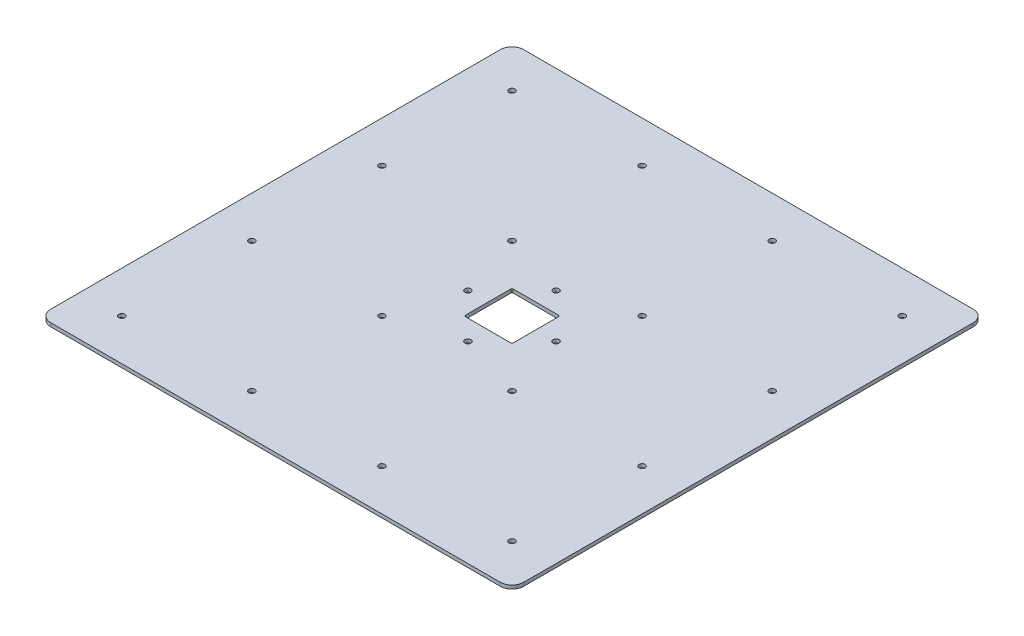
SolidWorks part; units mm, degrees
material "Stainless Steel (ferritic)"
ref_plane "Front Plane" through (0, 0, 0) normal (0, 0, 1) x (1, 0, 0)
ref_plane "Top Plane" through (0, 0, 0) normal (0, 1, 0) x (1, 0, 0)
ref_plane "Right Plane" through (0, 0, 0) normal (1, 0, 0) x (0, 0, -1)
sketch "Sketch1" plane through (0, 0, 0) normal (0, 1, 0) x (1, 0, 0)
  line L1 (-200, 200) -> (200, 200)
  line L2 (-200, 200) -> (-200, -200)
  line L3 (-200, -200) -> (200, -200)
  line L4 (200, 200) -> (200, -200)
  line L5 (-200, 200) -> (200, -200) construction
  line L6 (-200, -200) -> (200, 200) construction
  point P0 (0, 0)
  dimension "D1" = 400
  dimension "D2" = 400
extrude "Boss-Extrude1" add sketch "Sketch1" along normal blind 3
sketch "Sketch3" plane through (0, 3, 0) normal (0, 1, 0) x (1, 0, 0)
  line L1 (-19.25, 20.25) -> (19.25, 20.25)
  line L2 (-20.25, 19.25) -> (-20.25, -19.25)
  line L3 (-19.25, -20.25) -> (19.25, -20.25)
  line L4 (20.25, 19.25) -> (20.25, -19.25)
  line L5 (-20.25, 20.25) -> (20.25, -20.25) construction
  line L6 (-20.25, -20.25) -> (20.25, 20.25) construction
  arc A0 (19.25, -20.25) -> (20.25, -19.25) centre (19.25, -19.25) ccw
  arc A1 (-20.25, -19.25) -> (-19.25, -20.25) centre (-19.25, -19.25) ccw
  arc A2 (19.25, 20.25) -> (20.25, 19.25) centre (19.25, 19.25) cw
  arc A3 (-19.25, 20.25) -> (-20.25, 19.25) centre (-19.25, 19.25) ccw
  point P0 (0, 0)
  dimension "D3" = 1
  dimension "D1" = 40.5
  dimension "D2" = 40.5
extrude "Cut-Extrude1" cut sketch "Sketch3" against normal through all
sketch "Sketch4" plane through (0, 3, 0) normal (0, 1, 0) x (1, 0, 0)
  line L0 (0, 0) -> (-37.25, 0) construction
  line L1 (-20.25, 19.25) -> (-20.25, -19.25) construction
  line L2 (0, 0) -> (-37.25, 0) construction
  line L3 (0, 0) -> (0, 37.25) construction
  circle A0 centre (-37.25, 0) radius 2.58
  circle A1 centre (0, 37.25) radius 2.58
  circle A2 centre (37.25, 0) radius 2.58
  circle A3 centre (0, -37.25) radius 2.58
  point P4 (-20.25, 0)
  dimension "D1" = 5.16
  dimension "D2" = 17
  dimension "D4" = 90
  dimension "D5" = 37.25
  dimension "D3" = 4
extrude "Cut-Extrude2" cut sketch "Sketch4" against normal through all
sketch "Sketch9" plane through (0, 3, 0) normal (0, 1, 0) x (1, 0, 0)
  line L0 (-165, 165) -> (-200, 165) construction
  line L1 (-200, 200) -> (-200, -200) construction
  line L2 (-165, 165) -> (-165, 200) construction
  line L3 (200, 200) -> (-200, 200) construction
  line L4 (-165, 165) -> (-55, 165) construction
  line L5 (-165, 165) -> (-165, 55) construction
  line L6 (165, 165) -> (200, 165) construction
  line L7 (200, -200) -> (200, 200) construction
  line L8 (165, -165) -> (165, -200) construction
  line L9 (-200, -200) -> (200, -200) construction
  circle A0 centre (-165, 165) radius 2.58
  circle A1 centre (-55, 165) radius 2.58
  circle A2 centre (55, 165) radius 2.58
  circle A3 centre (165, 165) radius 2.58
  circle A4 centre (-55, 55) radius 2.58
  circle A5 centre (55, 55) radius 2.58
  circle A6 centre (165, 55) radius 2.58
  circle A7 centre (-55, -55) radius 2.58
  circle A8 centre (55, -55) radius 2.58
  circle A9 centre (165, -55) radius 2.58
  circle A10 centre (-55, -165) radius 2.58
  circle A11 centre (55, -165) radius 2.58
  circle A12 centre (165, -165) radius 2.58
  circle A13 centre (-165, 55) radius 2.58
  circle A14 centre (-165, -55) radius 2.58
  circle A15 centre (-165, -165) radius 2.58
  dimension "D1" = 5.16
  dimension "D2" = 35
  dimension "D5" = 90
  dimension "D6" = 110
  dimension "D7" = 110
  dimension "D3" = 4
  dimension "D4" = 4
extrude "Cut-Extrude4" cut sketch "Sketch9" against normal through all
fillet "Fillet1" radius 10 4 edges at (-200, 1.5, 200) (-200, 1.5, -200) (200, 1.5, -200) (200, 1.5, 200)
